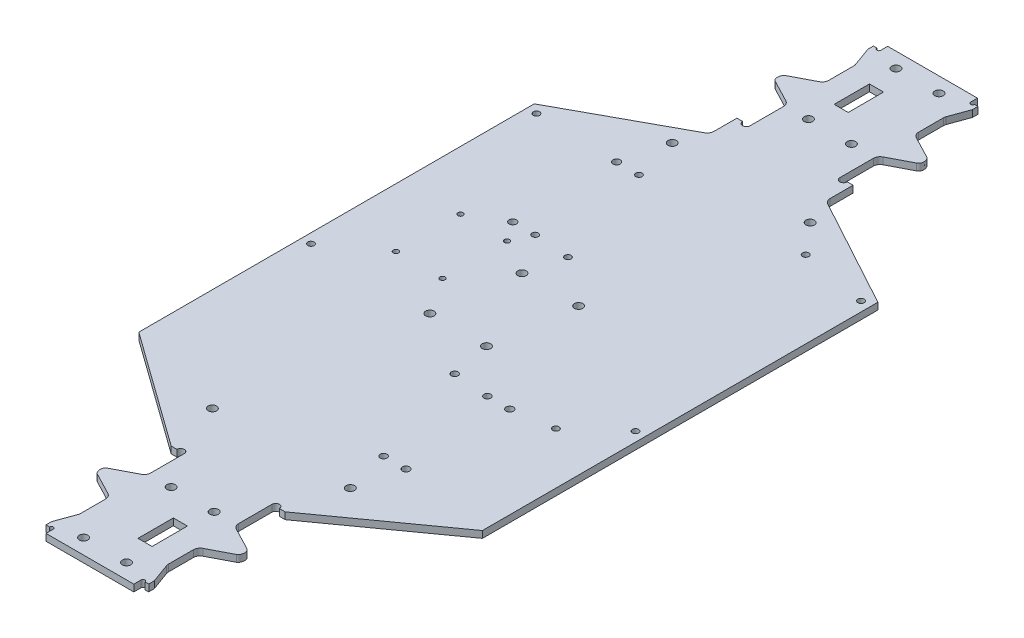
SolidWorks part; units mm, degrees
ref_plane "Front Plane" through (0, 0, 0) normal (0, 0, 1) x (1, 0, 0)
ref_plane "Top Plane" through (0, 0, 0) normal (0, 1, 0) x (1, 0, 0)
ref_plane "Right Plane" through (0, 0, 0) normal (1, 0, 0) x (0, 0, -1)
sketch "Sketch1" plane through (0, 0, 0) normal (0, 1, 0) x (1, 0, 0)
  line L0 (20.9042, 21.0573) -> (20.9042, 9.5003)
  line L1 (-20.9042, 36.9061) -> (20.9042, 36.9061)
  line L2 (0, 36.9061) -> (0, -449.5929) construction
  line L3 (20.9042, 36.9061) -> (20.9042, 33.6803)
  line L4 (22.7076, 33.6803) -> (24.3586, 33.6803)
  line L5 (24.3586, 33.6803) -> (24.3586, 31.1403)
  line L6 (24.3586, 31.1403) -> (21.0944, 22.1398)
  line L7 (20.9042, 7.5746) -> (20.9042, -9.6974) construction
  line L8 (20.9042, -1.0614) -> (34.1122, -1.0614) construction
  line L9 (22.6119, -8.8075) -> (32.9038, -3.4443)
  line L10 (22.6119, 6.6847) -> (32.9038, 1.3215)
  line L11 (20.9042, -11.6231) -> (20.9042, -27.1726)
  line L12 (24.384, -27.1726) -> (27.051, -27.1726)
  line L13 (27.051, -27.1726) -> (27.051, -37.8598)
  line L14 (28.7069, -40.6479) -> (80.01, -68.6007)
  line L15 (80.01, -68.6007) -> (80.01, -252.7507)
  line L16 (26.5303, -291.1425) -> (80.01, -252.7507)
  line L17 (26.5303, -291.1425) -> (23.8379, -291.1425)
  line L19 (20.4343, -306.692) -> (20.4343, -291.1425)
  line L20 (20.4515, -355.5288) -> (-20.4515, -355.5288)
  line L21 (-20.4343, -339.3725) -> (-20.4343, -327.8155)
  line L22 (22.142, -324.9998) -> (32.4339, -319.6366)
  line L23 (22.142, -309.5077) -> (32.4339, -314.8709)
  line L24 (23.8887, -349.4554) -> (20.6245, -340.4549)
  line L25 (23.8834, -351.9954) -> (23.8887, -349.4554)
  line L26 (22.2377, -352.1279) -> (23.8834, -351.9954)
  line L27 (20.4515, -355.5288) -> (20.4515, -352.303)
  line L28 (-20.4515, -355.5288) -> (-20.4515, -352.303)
  line L29 (20.4343, -339.3725) -> (20.4343, -327.8155)
  line L30 (-22.2377, -352.1279) -> (-23.8834, -351.9954)
  line L31 (-23.8834, -351.9954) -> (-23.8887, -349.4554)
  line L32 (-23.8887, -349.4554) -> (-20.6245, -340.4549)
  line L33 (-22.142, -309.5077) -> (-32.4339, -314.8709)
  line L34 (-22.142, -324.9998) -> (-32.4339, -319.6366)
  line L35 (-20.4343, -306.692) -> (-20.4343, -291.1425)
  line L36 (-26.5303, -291.1425) -> (-23.8379, -291.1425)
  line L37 (-26.5303, -291.1425) -> (-80.01, -252.7507)
  line L38 (-80.01, -68.6007) -> (-80.01, -252.7507)
  line L39 (-28.7069, -40.6479) -> (-80.01, -68.6007)
  line L40 (-27.051, -27.1726) -> (-27.051, -37.8598)
  line L41 (-24.384, -27.1726) -> (-27.051, -27.1726)
  line L42 (-20.9042, -11.6231) -> (-20.9042, -27.1726)
  line L43 (-20.9042, 36.9061) -> (-20.9042, 33.6803)
  line L44 (-20.9042, -1.0614) -> (-34.1122, -1.0614) construction
  line L45 (-20.9042, 7.5746) -> (-20.9042, -9.6974) construction
  line L46 (-22.6119, 6.6847) -> (-32.9038, 1.3215)
  line L47 (-22.6119, -8.8075) -> (-32.9038, -3.4443)
  line L48 (-24.3586, 31.1403) -> (-21.0944, 22.1398)
  line L49 (-24.3586, 33.6803) -> (-24.3586, 31.1403)
  line L50 (-22.7076, 33.6803) -> (-24.3586, 33.6803)
  line L51 (-20.9042, 21.0573) -> (-20.9042, 9.5003)
  arc A0 (20.9042, 33.6803) -> (22.7076, 33.6803) centre (21.8059, 33.6803) ccw
  arc A1 (20.9042, 21.0573) -> (21.0944, 22.1398) centre (24.0792, 21.0573) cw
  arc A2 (22.6119, 6.6847) -> (20.9042, 9.5003) centre (24.0792, 9.5003) cw
  arc A3 (20.9042, -27.1726) -> (24.384, -27.1726) centre (22.6441, -27.1726) ccw
  arc A4 (28.7069, -40.6479) -> (27.051, -37.8598) centre (30.226, -37.8598) cw
  arc A5 (20.9042, -11.6231) -> (22.6119, -8.8075) centre (24.0792, -11.6231) cw
  arc A6 (23.8379, -291.1425) -> (20.4343, -291.1425) centre (22.1361, -291.1425) ccw
  arc A7 (20.4343, -306.692) -> (22.142, -309.5077) centre (23.6093, -306.692) ccw
  arc A8 (22.142, -324.9998) -> (20.4343, -327.8155) centre (23.6093, -327.8155) ccw
  arc A9 (20.4343, -339.3725) -> (20.6245, -340.4549) centre (23.6093, -339.3725) ccw
  arc A10 (20.4515, -352.303) -> (22.2377, -352.1279) centre (21.336, -352.1279) cw
  arc A11 (-20.4515, -352.303) -> (-22.2377, -352.1279) centre (-21.336, -352.1279) ccw
  arc A12 (-20.4343, -339.3725) -> (-20.6245, -340.4549) centre (-23.6093, -339.3725) cw
  arc A13 (-22.142, -324.9998) -> (-20.4343, -327.8155) centre (-23.6093, -327.8155) cw
  arc A14 (-20.4343, -306.692) -> (-22.142, -309.5077) centre (-23.6093, -306.692) cw
  arc A15 (-23.8379, -291.1425) -> (-20.4343, -291.1425) centre (-22.1361, -291.1425) cw
  arc A16 (-28.7069, -40.6479) -> (-27.051, -37.8598) centre (-30.226, -37.8598) ccw
  arc A17 (-20.9042, -27.1726) -> (-24.384, -27.1726) centre (-22.6441, -27.1726) cw
  arc A18 (-20.9042, -11.6231) -> (-22.6119, -8.8075) centre (-24.0792, -11.6231) ccw
  arc A19 (-22.6119, 6.6847) -> (-20.9042, 9.5003) centre (-24.0792, 9.5003) ccw
  arc A20 (-20.9042, 21.0573) -> (-21.0944, 22.1398) centre (-24.0792, 21.0573) ccw
  arc A21 (-20.9042, 33.6803) -> (-22.7076, 33.6803) centre (-21.8059, 33.6803) cw
  spline S0 degree 3 poles (32.9038, 1.3215) (33.6149, 0.9509) (34.4634, -1.1376) (33.9071, -2.9215) (32.9038, -3.4443) knots 0 0 0 0 0.5 1 1 1 1
  spline S1 degree 3 poles (32.4339, -319.6366) (33.145, -319.2661) (33.9935, -317.1776) (33.4372, -315.3937) (32.4339, -314.8709) knots 0 0 0 0 0.5 1 1 1 1
  spline S2 degree 3 poles (-32.4339, -319.6366) (-33.145, -319.2661) (-33.9935, -317.1776) (-33.4372, -315.3937) (-32.4339, -314.8709) knots 0 0 0 0 0.5 1 1 1 1
  spline S3 degree 3 poles (-32.9038, 1.3215) (-33.6149, 0.9509) (-34.4634, -1.1376) (-33.9071, -2.9215) (-32.9038, -3.4443) knots 0 0 0 0 0.5 1 1 1 1
  point P8 (0, 36.9061)
  point P9 (0, 36.9061)
  point P22 (20.9042, 21.6153)
  point P34 (27.051, -39.7456)
  point P48 (0, -355.5288)
  point P69 (20.9042, -351.3667)
  point P87 (-20.9042, -351.3667)
  point P98 (-27.051, -39.7456)
  point P119 (-20.9042, 21.6153)
  dimension "D3" = 0.9017
  dimension "D10" = 3.175
  dimension "D11" = 3.175
  dimension "D13" = 1.7399
  dimension "D18" = 3.175
  dimension "D19" = 3.175
  dimension "D24" = 1.7018
  dimension "D26" = 3.175
  dimension "D28" = 5.628
  dimension "D30" = 3.175
  dimension "D32" = 3.175
  dimension "D36" = 0.9017
  dimension "D1" = 41.8084
  dimension "D2" = 3.2258
  dimension "D4" = 1.651
  dimension "D5" = 2.54
  dimension "D6" = 12.065
  dimension "D7" = 11.557
  dimension "D8" = 17.272
  dimension "D9" = 13.208
  dimension "D12" = 17.4752
  dimension "D14" = 2.667
  dimension "D15" = 12.573
  dimension "D17" = 80.01
  dimension "D20" = 184.15
  dimension "D22" = 26.5303
  dimension "D23" = 2.6924
  dimension "D25" = 15.5495
  dimension "D27" = 11.6055
  dimension "D29" = 11.6055
  dimension "D31" = 11.557
  dimension "D33" = 9.5741
  dimension "D34" = 2.54
  dimension "D35" = 1.651
  dimension "D37" = 3.2258
extrude "Boss-Extrude1" add sketch "Sketch1" along normal blind 3.175
sketch "Sketch3" plane through (0, 3.175, 0) normal (0, 1, 0) x (1, 0, 0)
  line L0 (0, 45.4183) -> (0, -355.5288) construction
  line L1 (20.9042, 36.9061) -> (-20.9042, 36.9061) construction
  line L2 (-20.4515, -355.5288) -> (20.4515, -355.5288) construction
  line L3 (-80.01, -68.6007) -> (-80.01, -252.7507) construction
  line L4 (-9.9822, 17.4751) -> (-3.429, 17.4751)
  line L5 (-9.9822, 17.4751) -> (-9.9822, 1.0159)
  line L6 (-9.9822, 1.0159) -> (-3.429, 1.0159)
  line L7 (-3.429, 17.4751) -> (-3.429, 1.0159)
  line L8 (-20.9042, 21.0573) -> (-20.9042, 9.5003) construction
  line L9 (20.4343, -339.3725) -> (20.4343, -327.8155) construction
  line L10 (2.9591, -319.6386) -> (9.5123, -319.6386)
  line L11 (2.9591, -319.6386) -> (2.9591, -336.0978)
  line L12 (2.9591, -336.0978) -> (9.5123, -336.0978)
  line L13 (9.5123, -319.6386) -> (9.5123, -336.0978)
  line L14 (-75.565, -72.0073) -> (-78.0137, -67.513) construction
  line L15 (-28.7069, -40.6479) -> (-80.01, -68.6007) construction
  line L16 (-28.7069, -40.6479) -> (-80.01, -68.6007) construction
  line L17 (80.01, -252.7507) -> (80.01, -68.6007) construction
  line L18 (-80.01, -68.6007) -> (-80.01, -252.7507) construction
  line L19 (80.01, -252.7507) -> (80.01, -68.6007) construction
  circle A0 centre (-10.0076, 29.8703) radius 1.9685
  circle A1 centre (10.0076, 29.8703) radius 1.9685
  circle A2 centre (-10.0076, -10.9221) radius 1.9685
  circle A3 centre (10.0076, -10.9221) radius 1.9685
  circle A4 centre (-32.1183, -52.2411) radius 1.9685
  circle A5 centre (32.1183, -52.2411) radius 1.9685
  circle A6 centre (-10.0076, -348.493) radius 1.9685
  circle A7 centre (10.0076, -348.493) radius 1.9685
  circle A8 centre (10.0076, -307.7006) radius 1.9685
  circle A9 centre (-10.0076, -307.7006) radius 1.9685
  circle A10 centre (-32.1183, -266.3816) radius 1.9685
  circle A11 centre (32.1183, -266.3816) radius 1.9685
  circle A12 centre (-37.4094, -72.8713) radius 1.7018
  circle A13 centre (-26.9827, -72.8713) radius 1.4605
  circle A14 centre (-26.9827, -121.2075) radius 1.4605
  circle A15 centre (-37.4094, -121.2075) radius 1.7018
  circle A16 centre (37.4094, -245.7515) radius 1.7018
  circle A17 centre (26.9827, -245.7515) radius 1.5875
  circle A18 centre (37.4094, -197.4153) radius 1.7018
  circle A19 centre (26.9827, -197.4153) radius 1.5875
  circle A20 centre (-10.3283, -122.608) radius 1.4605
  circle A21 centre (10.3545, -196.006) radius 1.5875
  circle A22 centre (-14.519, -139.7926) radius 1.9685
  circle A23 centre (11.8462, -139.7926) radius 1.9685
  circle A24 centre (6.6041, -177.4533) radius 1.9685
  circle A25 centre (-19.7611, -177.4533) radius 1.9685
  circle A26 centre (75.565, -72.0073) radius 1.4605
  circle A27 centre (-75.565, -72.0073) radius 1.4605
  circle A28 centre (-75.565, -177.0363) radius 1.4605
  circle A29 centre (75.565, -177.0363) radius 1.4605
  circle A30 centre (44.0563, -66.2624) radius 1.4732
  circle A31 centre (55.9943, -194.5324) radius 1.4732
  circle A32 centre (-52.6798, -130.2686) radius 1.2065
  circle A33 centre (-30.9882, -130.2686) radius 1.2065
  circle A34 centre (-52.6798, -160.3676) radius 1.2065
  circle A35 centre (-30.9882, -160.3676) radius 1.2065
  dimension "D1" = 3.937
  dimension "D2" = 3.937
  dimension "D5" = 20.0152
  dimension "D6" = 20.0152
  dimension "D7" = 3.937
  dimension "D8" = 64.2366
  dimension "D9" = 46.863
  dimension "D10" = 3.937
  dimension "D11" = 20.0152
  dimension "D12" = 20.0152
  dimension "D15" = 46.863
  dimension "D16" = 64.2366
  dimension "D18" = 3.4036
  dimension "D19" = 2.921
  dimension "D20" = 10.4267
  dimension "D21" = 21.2598
  dimension "D22" = 48.3362
  dimension "D23" = 10.4267
  dimension "D24" = 3.4036
  dimension "D25" = 3.175
  dimension "D17" = 21.2979
  dimension "D26" = 21.2979
  dimension "D27" = 10.4267
  dimension "D28" = 21.2598
  dimension "D29" = 10.4267
  dimension "D30" = 48.3362
  dimension "D31" = 2.921
  dimension "D32" = 52.451
  dimension "D33" = 16.7132
  dimension "D34" = 3.175
  dimension "D35" = 52.451
  dimension "D36" = 16.6878
  dimension "D37" = 3.937
  dimension "D38" = 26.3652
  dimension "D39" = 26.3652
  dimension "D40" = 3.937
  dimension "D41" = 22.3774
  dimension "D42" = 68.072
  dimension "D43" = 3.937
  dimension "D44" = 43.18
  dimension "D45" = 38.0238
  dimension "D46" = 3.937
  dimension "D47" = 16.4592
  dimension "D48" = 6.5532
  dimension "D14" = 40.7924
  dimension "D49" = 40.7924
  dimension "D56" = 2.921
  dimension "D57" = 4.445
  dimension "D58" = 105.029
  dimension "D60" = 5.1181
  dimension "D61" = 90
  dimension "D62" = 2.9464
  dimension "D64" = 128.27
  dimension "D65" = 35.9537
  dimension "D66" = 18.415
  dimension "D67" = 2.413
  dimension "D70" = 20.4442
  dimension "D71" = 17.7564
  dimension "D74" = 2.921
  dimension "D75" = 2.921
  dimension "D76" = 42.6006
  dimension "D3" = 7.0358
  dimension "D13" = 7.0358
  dimension "D50" = 19.431
  dimension "D51" = 10.922
  dimension "D52" = 6.5532
  dimension "D53" = 16.4592
  dimension "D54" = 10.922
  dimension "D55" = 19.431
  dimension "D59" = 105.029
  dimension "D63" = 11.938
  dimension "D68" = 21.6916
  dimension "D69" = 30.099
  dimension "D72" = 160.02
  dimension "D73" = 24.0157
  dimension "D77" = 42.6006
extrude "Cut-Extrude1" cut sketch "Sketch3" against normal through all
sketch "Sketch4" [suppressed] plane through (0, 3.175, 0) normal (0, 1, 0) x (1, 0, 0)
  line L0 (-20.9042, -16.1291) -> (20.9042, -16.1291)
  line L1 (-20.9042, -11.6231) -> (-20.9042, -27.1726) construction
  line L2 (20.9042, -27.1726) -> (20.9042, -11.6231) construction
  line L3 (-20.4343, -302.4936) -> (20.4343, -302.4936)
  line L4 (-20.4343, -291.1425) -> (-20.4343, -306.692) construction
  line L5 (20.4343, -306.692) -> (20.4343, -291.1425) construction
  line L6 (-20.4515, -355.5288) -> (20.4515, -355.5288) construction
  line L7 (20.9042, 36.9061) -> (-20.9042, 36.9061) construction
  dimension "D1" = 53.0352
  dimension "D2" = 53.0352
sketch "Sketch5" [suppressed] plane through (0, 0, 0) normal (0, -1, 0) x (1, 0, 0)
  line L0 (20.4343, 295.855) -> (-20.4343, 295.855) construction
  line L1 (20.4343, 306.692) -> (20.4343, 291.1425) construction
  line L2 (-20.4343, 291.1425) -> (-20.4343, 306.692) construction
  line L3 (20.9042, 19.3979) -> (-20.9042, 19.3979) construction
  line L4 (20.9042, 27.1726) -> (20.9042, 11.6231) construction
  line L5 (-20.9042, 11.6231) -> (-20.9042, 27.1726) construction
  line L6 (0, 19.3979) -> (0, 295.855) construction
